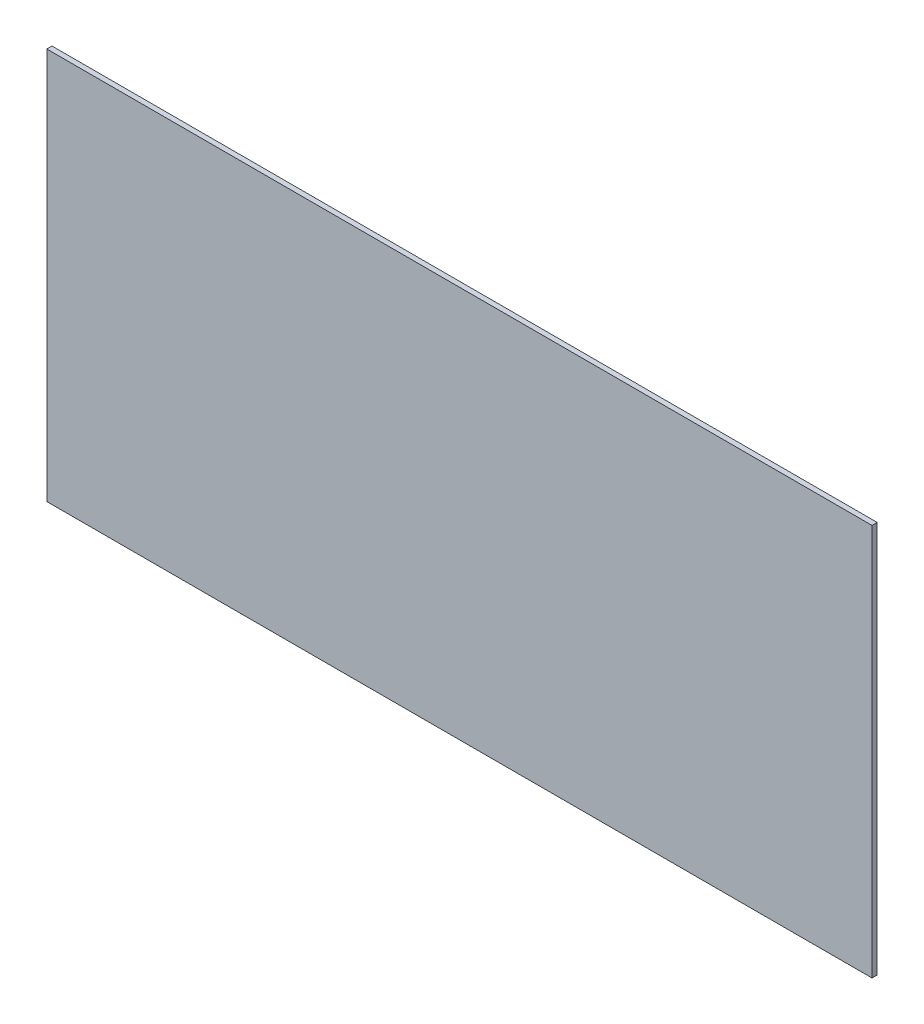
SolidWorks part; units mm, degrees
material "铜"
ref_plane "前视基准面" through (0, 0, 0) normal (0, 0, 1) x (1, 0, 0)
ref_plane "上视基准面" through (0, 0, 0) normal (0, 1, 0) x (1, 0, 0)
ref_plane "右视基准面" through (0, 0, 0) normal (1, 0, 0) x (0, 0, -1)
sketch "草图1" plane through (0, 0, 0) normal (0, 0, 1) x (1, 0, 0)
  line L1 (0, 0) -> (160, 0)
  line L2 (0, 0) -> (0, 76)
  line L3 (0, 76) -> (160, 76)
  line L4 (160, 0) -> (160, 76)
  dimension "D1" = 160
  dimension "D2" = 76
extrude "凸台-拉伸1" add sketch "草图1" along normal blind 1
